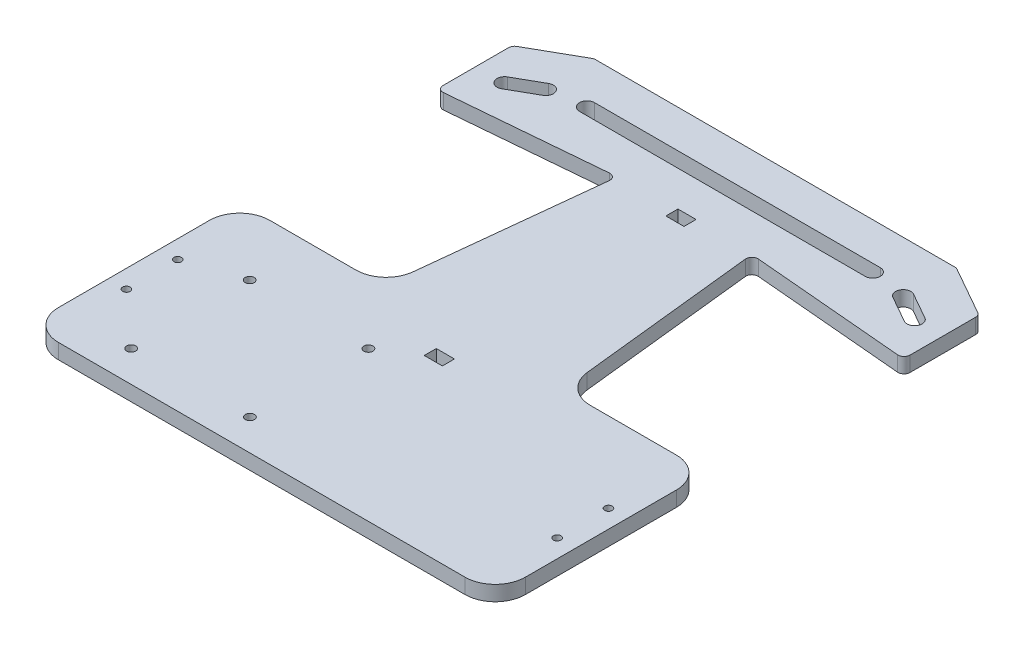
SolidWorks part; units mm, degrees
ref_plane "Front Plane" through (0, 0, 0) normal (0, 0, 1) x (1, 0, 0)
ref_plane "Top Plane" through (0, 0, 0) normal (0, 1, 0) x (1, 0, 0)
ref_plane "Right Plane" through (0, 0, 0) normal (1, 0, 0) x (0, 0, -1)
sketch "Sketch4" plane through (0, 0, 0) normal (0, 1, 0) x (1, 0, 0)
  line L1 (67.3069, -98.0013) -> (-67.3069, -98.0013)
  line L7 (-71.3069, -28.0013) -> (-71.3069, -54.5013) construction
  line L10 (38.7863, -28.0013) -> (67.3069, -28.0013)
  line L13 (77.3069, -38.0013) -> (77.3069, -88.0013)
  line L14 (0, 95) -> (0, -105.0286) construction
  line L15 (28.844, -19.0737) -> (22.2568, 41.9987)
  line L22 (71.3069, -28.0013) -> (71.3069, -54.5013) construction
  line L33 (-28.844, -19.0737) -> (-22.2568, 41.9987)
  line L34 (-77.3069, -38.0013) -> (-77.3069, -88.0013)
  line L35 (-38.7863, -28.0013) -> (-67.3069, -28.0013)
  line L37 (22.2568, 41.9987) -> (75.1326, 37.3726)
  line L38 (77.3069, 39.365) -> (77.3069, 62.1824)
  line L39 (77.3069, 62.1824) -> (60, 71.9987)
  line L40 (60, 71.9987) -> (-60, 71.9987)
  line L41 (22.2568, 41.9987) -> (94.4566, 41.9987) construction
  line L42 (-22.2568, 41.9987) -> (-75.1326, 37.3726)
  line L43 (-77.3069, 39.365) -> (-77.3069, 62.1824)
  line L44 (-77.3069, 62.1824) -> (-60, 71.9987)
  line L45 (-47.3069, 56.9987) -> (47.3069, 56.9987) construction
  line L46 (-47.3069, 59.4987) -> (47.3069, 59.4987)
  line L47 (-47.3069, 54.4987) -> (47.3069, 54.4987)
  line L48 (-59.1746, 55.222) -> (-67.8729, 50.2884) construction
  line L49 (-57.9412, 53.0474) -> (-66.6395, 48.1139)
  line L50 (-60.408, 57.3966) -> (-69.1063, 52.463)
  line L51 (59.1746, 55.222) -> (67.8729, 50.2884) construction
  line L52 (57.9412, 53.0474) -> (66.6395, 48.1139)
  line L53 (60.408, 57.3966) -> (69.1063, 52.463)
  line L55 (-3, 42.8072) -> (3, 42.8072)
  line L56 (-3, 42.8072) -> (-3, 38.8072)
  line L57 (-3, 38.8072) -> (3, 38.8072)
  line L58 (3, 42.8072) -> (3, 38.8072)
  line L59 (-3, 42.8072) -> (3, 38.8072) construction
  line L60 (-3, 38.8072) -> (3, 42.8072) construction
  line L61 (-3, -37.1928) -> (3, -37.1928)
  line L62 (-3, -37.1928) -> (-3, -41.1928)
  line L63 (-3, -41.1928) -> (3, -41.1928)
  line L64 (3, -37.1928) -> (3, -41.1928)
  line L65 (-3, -37.1928) -> (3, -41.1928) construction
  line L66 (-3, -41.1928) -> (3, -37.1928) construction
  circle A1 centre (71.3069, -54.5013) radius 1.25
  circle A2 centre (71.3069, -71.5013) radius 1.25
  circle A8 centre (-71.3069, -71.5013) radius 1.25
  circle A9 centre (-71.3069, -54.5013) radius 1.25
  arc A10 (-77.3069, -38.0013) -> (-67.3069, -28.0013) centre (-67.3069, -38.0013) cw
  arc A11 (-38.7863, -28.0013) -> (-28.844, -19.0737) centre (-38.7863, -18.0013) ccw
  arc A12 (67.3069, -28.0013) -> (77.3069, -38.0013) centre (67.3069, -38.0013) cw
  arc A13 (67.3069, -98.0013) -> (77.3069, -88.0013) centre (67.3069, -88.0013) ccw
  arc A14 (-77.3069, -88.0013) -> (-67.3069, -98.0013) centre (-67.3069, -88.0013) ccw
  arc A15 (28.844, -19.0737) -> (38.7863, -28.0013) centre (38.7863, -18.0013) ccw
  arc A16 (-47.3069, 59.4987) -> (-47.3069, 54.4987) centre (-47.3069, 56.9987) ccw
  arc A17 (47.3069, 54.4987) -> (47.3069, 59.4987) centre (47.3069, 56.9987) ccw
  arc A18 (-57.9412, 53.0474) -> (-60.408, 57.3966) centre (-59.1746, 55.222) ccw
  arc A19 (-69.1063, 52.463) -> (-66.6395, 48.1139) centre (-67.8729, 50.2884) ccw
  arc A20 (57.9412, 53.0474) -> (60.408, 57.3966) centre (59.1746, 55.222) cw
  arc A21 (69.1063, 52.463) -> (66.6395, 48.1139) centre (67.8729, 50.2884) cw
  arc A22 (-75.1326, 37.3726) -> (-77.3069, 39.365) centre (-75.3069, 39.365) cw
  arc A23 (75.1326, 37.3726) -> (77.3069, 39.365) centre (75.3069, 39.365) ccw
  circle A24 centre (-53.5269, -87.7013) radius 1.5
  circle A25 centre (-53.5269, -48.4613) radius 1.5
  circle A26 centre (-14.2169, -48.4613) radius 1.5
  circle A27 centre (-14.2169, -87.7013) radius 1.5
  point P0 (0, 0)
  point P8 (77.3069, -28.0013)
  point P14 (77.3069, -98.0013)
  point P18 (-77.3069, -98.0013)
  point P23 (29.8069, -28.0013)
  point P36 (-47.3069, 56.9987)
  point P43 (0, 71.9987)
  point P44 (47.3069, 56.9987)
  point P47 (0, 56.9987)
  point P49 (0, -98.0013)
  point P51 (-77.3069, -28.0013)
  point P54 (-29.8069, -28.0013)
  point P58 (-59.1746, 55.222)
  point P59 (-67.8729, 50.2884)
  point P60 (-63.5238, 52.7552)
  point P69 (63.5238, 52.7552)
  point P74 (0, 40.8072)
  point P79 (0, -39.1928)
  point P86 (-77.3069, 37.1824)
  point P89 (77.3069, 37.1824)
  dimension "D7" = 26.5
  dimension "D8" = 6
  dimension "D9" = 2.5
  dimension "D10" = 2.5
  dimension "D12" = 10
  dimension "D13" = 10
  dimension "D17" = 6
  dimension "D18" = 5
  dimension "D4" = 10
  dimension "D19" = 60
  dimension "D3" = 10
  dimension "D6" = 10
  dimension "D25" = 5
  dimension "D37" = 2
  dimension "D39" = 3
  dimension "D40" = 3
  dimension "D42" = 23.78
  dimension "D43" = 23.78
  dimension "D44" = 3
  dimension "D45" = 3
  dimension "D5" = 47.5
  dimension "D11" = 26.5
  dimension "D14" = 15
  dimension "D15" = 25
  dimension "D16" = 17
  dimension "D20" = 0
  dimension "D21" = 170
  dimension "D22" = 70
  dimension "D23" = 30
  dimension "D24" = 30
  dimension "D26" = 70
  dimension "D27" = 12
  dimension "D28" = 10
  dimension "D29" = 15
  dimension "D30" = 15
  dimension "D31" = 5
  dimension "D32" = 6
  dimension "D33" = 4
  dimension "D34" = 6
  dimension "D35" = 4
  dimension "D36" = 80
  dimension "D38" = 20.46
  dimension "D41" = 10.3
  dimension "D46" = 39.31
  dimension "D47" = 39.31
extrude "Boss-Extrude1" add sketch "Sketch4" along normal blind 5
fillet "Fillet2" radius 2 6 edges at (77.3069, 2.5, -62.1824) (60, 2.5, -71.9987) (-60, 2.5, -71.9987) (-77.3069, 2.5, -62.1824) (-22.2568, 2.5, -41.9987) (22.2568, 2.5, -41.9987)
